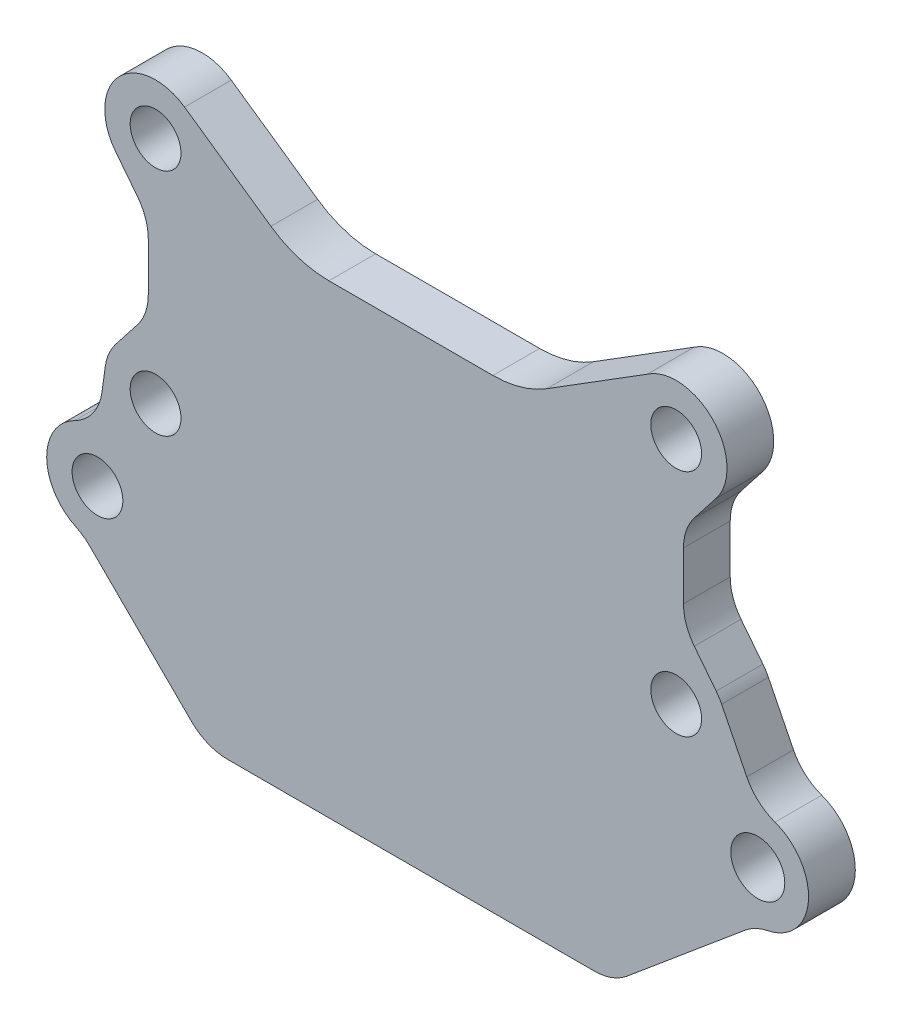
SolidWorks part; units mm, degrees
ref_plane "Front Plane" through (0, 0, 0) normal (0, 0, 1) x (1, 0, 0)
ref_plane "Top Plane" through (0, 0, 0) normal (0, 1, 0) x (1, 0, 0)
ref_plane "Right Plane" through (0, 0, 0) normal (1, 0, 0) x (0, 0, -1)
sketch "Sketch1" plane through (0, 0, 0) normal (0, 0, 1) x (1, 0, 0)
  line L0 (-18.8232, 25.0598) -> (-18.8232, -3.6422) construction
  line L1 (46.2643, -3.6422) -> (46.2643, 25.0598) construction
  line L2 (46.2643, 10.7088) -> (-18.8232, 10.7088) construction
  line L3 (-19.7352, 15.9265) -> (-23.8222, 21.1441)
  line L4 (-1.1351, 20.4907) -> (-15.197, 30.2726)
  line L5 (13.7205, 10.7088) -> (13.7205, 0) construction
  line L6 (26.9887, 20.4907) -> (42.6381, 30.2726)
  line L7 (47.1763, 15.9265) -> (51.2633, 21.1441)
  line L8 (-1.1351, 20.4907) -> (26.9887, 20.4907)
  line L9 (47.1763, 5.4912) -> (51.2633, 0.2735)
  line L10 (-19.7352, 5.4912) -> (-23.8222, 0.2735)
  line L11 (-19.7352, 15.9265) -> (-19.7352, 5.4912)
  line L12 (47.1763, 15.9265) -> (47.1763, 5.4912)
  line L13 (-25.1732, -3.6422) -> (-25.1732, -37.6595)
  line L14 (-25.1732, -37.6595) -> (52.6143, -37.6595)
  line L15 (52.6143, -3.6422) -> (52.6143, -37.6595)
  circle A0 centre (-18.8232, 25.0598) radius 3.175
  circle A1 centre (46.2643, 25.0598) radius 3.175
  arc A2 (-15.197, 30.2726) -> (-23.8222, 21.1441) centre (-18.8232, 25.0598) ccw
  arc A3 (51.2633, 21.1441) -> (42.6381, 30.2726) centre (46.2643, 25.0598) ccw
  arc A4 (52.6143, -3.6422) -> (51.2633, 0.2735) centre (46.2643, -3.6422) ccw
  circle A5 centre (46.2643, -3.6422) radius 3.175
  circle A6 centre (-18.8232, -3.6422) radius 3.175
  arc A7 (-23.8222, 0.2735) -> (-25.1732, -3.6422) centre (-18.8232, -3.6422) ccw
  dimension "D1" = 6.35
  dimension "D4" = 12.7
  dimension "D3" = 2
  dimension "D6" = 65.0875
  dimension "D7" = 28.702
  dimension "D2" = 2
  dimension "D5" = 2
extrude "Boss-Extrude1" add sketch "Sketch1" along normal blind 5.842
fillet "Fillet1" radius 6.35 4 edges at (-19.7352, 15.9265, 2.921) (-19.7352, 5.4912, 2.921) (47.1763, 15.9265, 2.921) (47.1763, 5.4912, 2.921)
fillet "Fillet2" radius 12.7 2 edges at (26.9887, 20.4907, 2.921) (-1.1351, 20.4907, 2.921)
sketch "Sketch2" plane through (0, 0, 5.842) normal (0, 0, 1) x (1, 0, 0)
  line L0 (-26.0852, -9.8644) -> (-25.1144, -2.7801)
  line L2 (-25.1732, -22.5644) -> (-25.1732, -22.4985)
  line L3 (-25.1732, -3.6422) -> (-25.1732, -37.6595) construction
  line L4 (56.4648, -22.5644) -> (52.6143, -22.5644)
  line L5 (52.6143, -37.6595) -> (52.6143, -3.6422) construction
  line L6 (56.4648, -9.8644) -> (51.9464, -0.8074)
  line L7 (-25.1732, -3.6422) -> (-25.1732, -37.6595)
  line L8 (52.6143, -37.6595) -> (52.6143, -21.2637)
  line L9 (52.6143, -11.165) -> (52.6143, -3.6422)
  line L10 (-26.0852, -22.5644) -> (-25.1732, -22.5644)
  circle A0 centre (-26.0852, -16.2144) radius 3.1742
  circle A1 centre (56.4648, -16.2144) radius 3.375
  arc A2 (-26.0852, -9.8644) -> (-26.0852, -22.5644) centre (-26.0852, -16.2144) ccw
  arc A3 (52.6143, -11.165) -> (52.6143, -21.2637) centre (56.4648, -16.2144) ccw
  arc A4 (-23.8222, 0.2735) -> (-25.1732, -3.6422) centre (-18.8232, -3.6422) ccw construction
  arc A5 (52.6143, -3.6422) -> (51.2633, 0.2735) centre (46.2643, -3.6422) ccw construction
  arc A6 (-25.1144, -2.7801) -> (-25.1732, -3.6422) centre (-18.8232, -3.6422) ccw
  arc A7 (52.6143, -3.6422) -> (51.2633, 0.2735) centre (46.2643, -3.6422) ccw
  arc A8 (56.4648, -22.5644) -> (56.4648, -9.8644) centre (56.4648, -16.2144) ccw
  arc A9 (-25.1732, -22.4985) -> (-25.1732, -9.9302) centre (-26.0852, -16.2144) ccw
  arc M16 (-23.8222, 0.2735) -> (-25.1732, -3.6422) centre (-18.8232, -3.6422) ccw
  line M17 (-25.1732, -3.6422) -> (-25.1732, -37.6595)
  line M19 (52.6143, -37.6595) -> (52.6143, -3.6422)
  arc M20 (52.6143, -3.6422) -> (51.2633, 0.2735) centre (46.2643, -3.6422) ccw
  dimension "D1" = 12.7
  dimension "D2" = 12.7
extrude "Boss-Extrude2" add sketch "Sketch2" against normal up to surface (5.842 mm away) contours L4 A8 L6 A1 M20 M19 | L0 A2 L10 A0 L7 M17 M16 up to face at (13.5817, 9.0563, 0)
sketch "Sketch3" plane through (0, 0, 5.842) normal (0, 0, 1) x (1, 0, 0)
  circle A0 centre (-26.0852, -16.2144) radius 3.1742
extrude "Cut-Extrude1" cut sketch "Sketch3" against normal through all
fillet "Fillet3" radius 6.35 4 edges at (56.4648, -9.8644, 2.921) (52.6143, -22.5644, 2.921) (-25.1732, -22.5644, 2.921) (-26.0852, -9.8644, 2.921)
sketch "Sketch4" plane through (0, 0, 5.842) normal (0, 0, 1) x (1, 0, 0)
  line L0 (-12.4732, -37.6595) -> (-27.0488, -23.1854)
  line L1 (-25.1732, -37.6595) -> (52.6143, -37.6595) construction
  line L2 (38.3268, -37.6595) -> (54.8885, -23.7967)
  line L3 (38.3268, -37.6595) -> (52.6143, -37.6595)
  line L4 (-25.1732, -27.6912) -> (-25.1732, -37.6595) construction
  line L5 (52.6143, -37.6595) -> (52.6143, -28.666) construction
  line L6 (-25.1732, -27.6912) -> (-25.1732, -37.6595)
  line L7 (-25.1732, -37.6595) -> (-12.4732, -37.6595)
  line L8 (52.6143, -37.6595) -> (52.6143, -28.666)
  arc A0 (-25.1732, -27.6912) -> (-28.8042, -21.9528) centre (-31.5232, -27.6912) ccw construction
  arc A1 (57.7145, -22.4402) -> (52.6143, -28.666) centre (58.9643, -28.666) ccw construction
  arc A2 (-25.1732, -27.6912) -> (-28.8042, -21.9528) centre (-31.5232, -27.6912) ccw
  arc A3 (54.8885, -23.7967) -> (52.6143, -28.666) centre (58.9643, -28.666) ccw
  arc M23 (-28.8042, -21.9528) -> (-25.1732, -27.6912) centre (-31.5232, -27.6912) cw
  line M24 (-25.1732, -27.6912) -> (-25.1732, -37.6595)
  line M25 (-25.1732, -37.6595) -> (52.6143, -37.6595)
  line M26 (52.6143, -37.6595) -> (52.6143, -28.666)
  arc M27 (52.6143, -28.666) -> (57.7145, -22.4402) centre (58.9643, -28.666) cw
  dimension "D1" = 50.8
  dimension "D2" = 12.7
extrude "Cut-Extrude2" cut sketch "Sketch4" against normal through all contours L0 M25 M23 M24 | L2 M25 M26 M27
fillet "Fillet4" radius 6.35 2 edges at (38.3268, -37.6595, 2.921) (-12.4732, -37.6595, 2.921)
